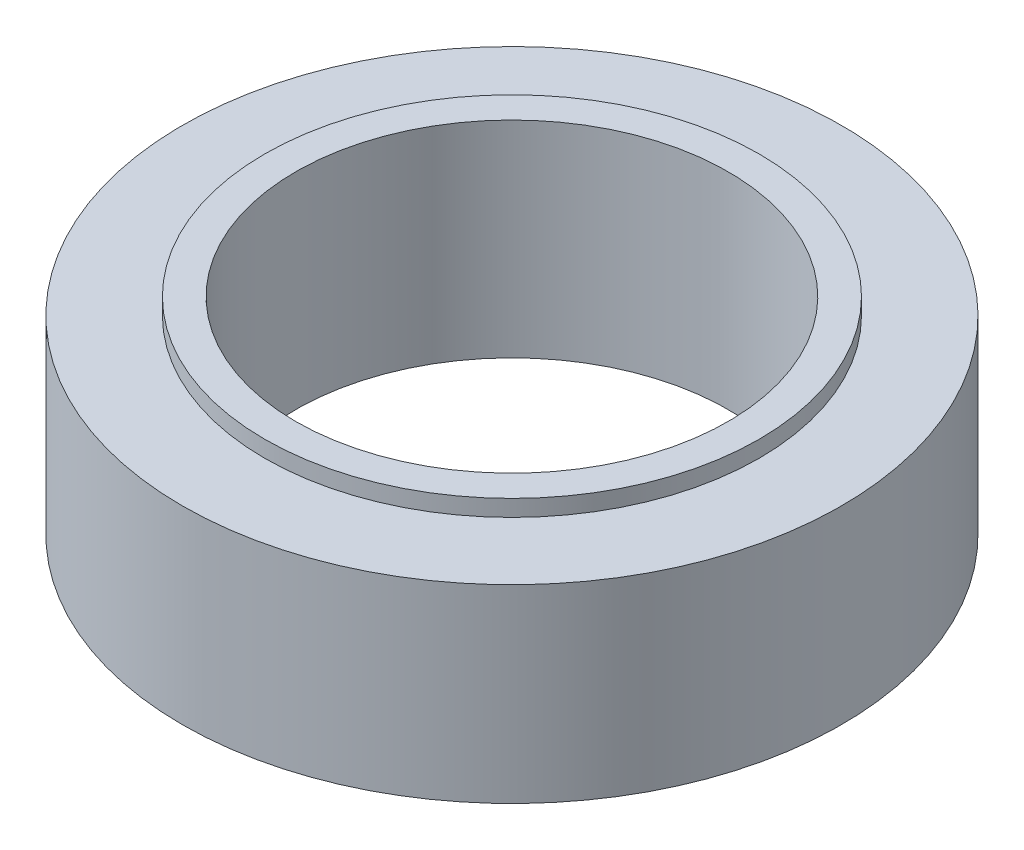
SolidWorks part; units mm, degrees
ref_plane "Alzado" through (0, 0, 0) normal (0, 0, 1) x (1, 0, 0)
ref_plane "Planta" through (0, 0, 0) normal (0, 1, 0) x (1, 0, 0)
ref_plane "Vista lateral" through (0, 0, 0) normal (1, 0, 0) x (0, 0, -1)
sketch "Croquis1" plane through (0, 0, 0) normal (0, 1, 0) x (1, 0, 0)
  circle A0 centre (0, 0) radius 4
  circle A1 centre (0, 0) radius 2.625
  dimension "D1" = 5.25
  dimension "D2" = 8
extrude "Saliente-Extruir1" add sketch "Croquis1" along normal blind 2.3
sketch "Croquis2" plane through (0, 2.3, 0) normal (0, 1, 0) x (1, 0, 0)
  circle A0 centre (0, 0) radius 3
  circle A1 centre (0, 0) radius 2.625 construction
  circle A2 centre (0, 0) radius 2.625
  dimension "D1" = 6
extrude "Saliente-Extruir2" add sketch "Croquis2" along normal blind 0.2
